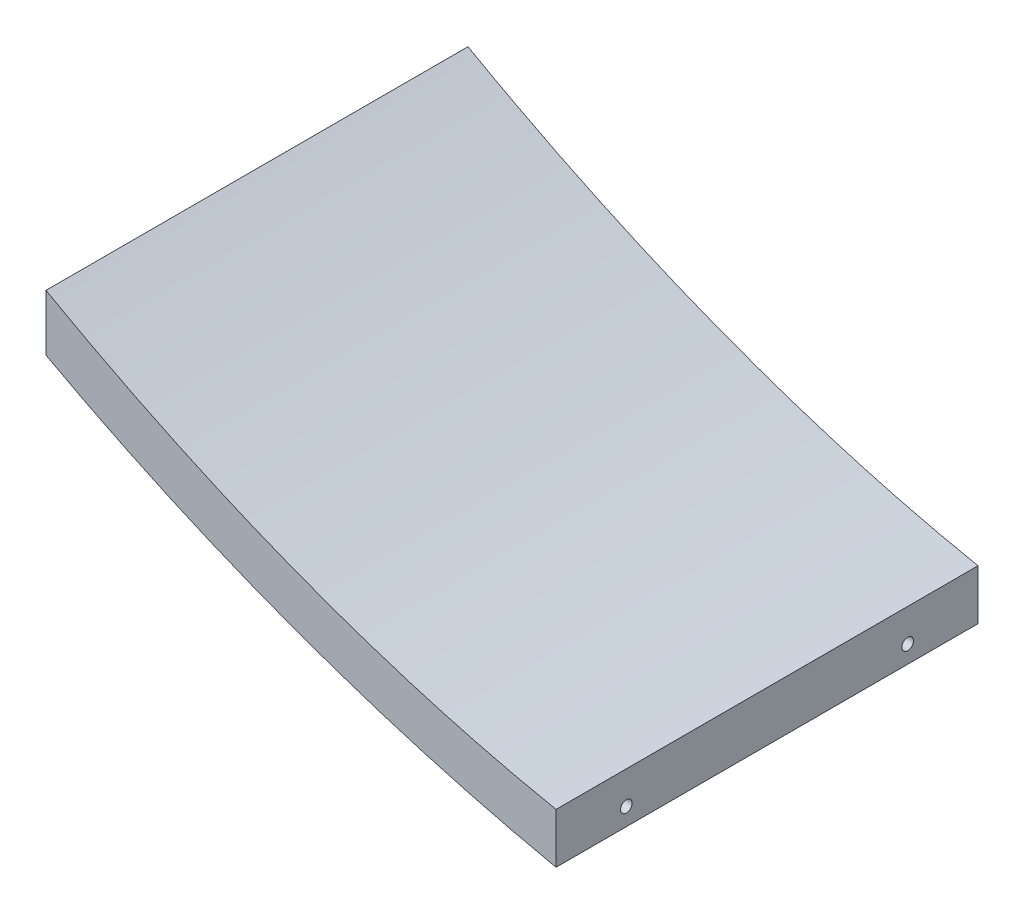
SolidWorks part; units mm, degrees
ref_plane "Front Plane" through (0, 0, 0) normal (0, 0, 1) x (1, 0, 0)
ref_plane "Top Plane" through (0, 0, 0) normal (0, 1, 0) x (1, 0, 0)
ref_plane "Right Plane" through (0, 0, 0) normal (1, 0, 0) x (0, 0, -1)
sketch "Sketch1" plane through (0, 0, 0) normal (0, 0, 1) x (1, 0, 0)
  line L0 (-80, -206.5) -> (-80, -192.5099) construction
  line L1 (-80, -206.5) -> (-80, -192.5099) construction
  line L2 (-80.2, -192.4699) -> (-80.2, -236.0949) construction
  line L3 (-80.2, -192.4699) -> (-80.2, -206.7286)
  line L4 (-225.2451, -137.1545) -> (-225.2451, -153.1407)
  arc A0 (-80.2, -206.7286) -> (-225.2451, -153.1407) centre (32.1304, 320.4019) cw
  spline S0 degree 3 poles (-2461.0702, -1470.5595) (486.3926, 66.7881) (343.88, -73.6971) (208.8273, -146.1009) (197.0951, -152.0818) (183.0206, -158.7616) (164.2523, -167.0094) (140.7912, -176.0823) (112.6357, -184.9909) (84.4784, -191.9202) (46.9336, -198.52) (0, -201.82) (-46.9336, -198.52) (-84.4784, -191.9202) (-112.6357, -184.9909) (-140.7912, -176.0823) (-164.2523, -167.0094) (-183.0206, -158.7616) (-197.0951, -152.0818) (-208.8273, -146.1009) (-343.882, -73.696) (-486.3971, 66.7925) (2461.2119, -1470.6333) knots 0.489359 0.489359 0.489359 0.489359 0.496147 0.496271 0.49652 0.496768 0.497017 0.497514 0.498011 0.498508 0.499006 0.5 0.500994 0.501492 0.501989 0.502486 0.502983 0.503232 0.50348 0.503729 0.503853 0.510641 0.510641 0.510641 0.510641 only from (225.2451, -137.1545) to (-225.2451, -137.1545) construction
  spline S1 degree 3 poles (225.2451, -137.1545) (222.9082, -138.4691) (218.2041, -141.0739) (208.8273, -146.1009) (197.0951, -152.0818) (183.0206, -158.7616) (164.2523, -167.0094) (140.7912, -176.0823) (112.6357, -184.9909) (84.4784, -191.9202) (46.9336, -198.52) (0, -201.82) (-46.9336, -198.52) (-84.4784, -191.9202) (-112.6357, -184.9909) (-140.7912, -176.0823) (-164.2523, -167.0094) (-183.0206, -158.7616) (-197.0951, -152.0818) (-208.8273, -146.1009) (-218.2041, -141.0739) (-222.9082, -138.4691) (-225.2451, -137.1545) knots 0.496023 0.496023 0.496023 0.496023 0.496147 0.496271 0.49652 0.496768 0.497017 0.497514 0.498011 0.498508 0.499006 0.5 0.500994 0.501492 0.501989 0.502486 0.502983 0.503232 0.50348 0.503729 0.503853 0.503977 0.503977 0.503977 0.503977
  spline S2 degree 1 poles (232.1039, -149.348) (-232.1039, -149.348) knots 0 0 1 1 construction
  spline S3 degree 3 poles (232.1039, -149.348) (229.7124, -150.6932) (224.8993, -153.3584) (215.2971, -158.5063) (204.0049, -164.2629) (193.9071, -169.0824) (186.2108, -172.607) (180.6635, -175.0744) (166.6796, -181.0726) (145.4403, -189.287) (116.4315, -198.4665) (87.3725, -205.6185) (48.5728, -212.4398) (0, -215.857) (-43.7507, -212.779) (-72.8929, -208.1647) (-92.2859, -204.4099) (-116.4665, -198.4554) (-145.4403, -189.287) (-169.567, -179.9559) (-188.8383, -171.4869) (-203.2759, -164.6346) (-215.2971, -158.5063) (-224.8993, -153.3584) (-229.7124, -150.6932) (-232.1039, -149.348) knots 0.496023 0.496023 0.496023 0.496023 0.496147 0.496271 0.49652 0.496731 0.496793 0.496917 0.497017 0.497514 0.498011 0.498508 0.499006 0.5 0.500994 0.501245 0.501493 0.501989 0.502486 0.502983 0.503232 0.50348 0.503729 0.503853 0.503977 0.503977 0.503977 0.503977 only from (232.1039, -149.348) to (-80.2, -206.7286) construction
  dimension "D1" = 13.9901
  dimension "D3" = 0.2
  dimension "D2" = 13.9901
extrude "Boss-Extrude1" add sketch "Sketch1" against normal up to surface (120 mm away) contours L3 S1 L4 A0
sketch "Sketch2" plane through (-80.2, 0, 0) normal (1, 0, 0) x (0, 0, -1)
  line L0 (60, -1206.7286) -> (60, 48793.2714) construction
  line L1 (120, -206.7286) -> (100, -206.7286) construction
  line L2 (120, -206.7286) -> (120, -201.7286) construction
  line L3 (120, -201.7286) -> (100, -201.7286) construction
  line L4 (100, -206.7286) -> (100, -201.7286) construction
  line L5 (120, -206.7286) -> (0, -206.7286) construction
  circle A0 centre (100, -201.7286) radius 1.65
  circle A1 centre (20, -201.7286) radius 1.65
  point P11 (60, -206.7286)
  dimension "D1" = 3.3
  dimension "D2" = 5
  dimension "D3" = 20
extrude "Cut-Extrude1" cut sketch "Sketch2" against normal through all
ref_plane "Plane1" through (-90.2, 0, 0) normal (1, 0, 0) x (0, 0, -1)
sketch "Sketch3" plane through (-90.2, 0, 0) normal (1, 0, 0) x (0, 0, -1)
  circle A0 centre (100, -201.7286) radius 3
  circle A1 centre (20, -201.7286) radius 3
  dimension "D1" = 6
extrude "Cut-Extrude2" cut sketch "Sketch3" against normal through all
equation "\"D2@Sketch1\"=\"D1@Sketch1\""
